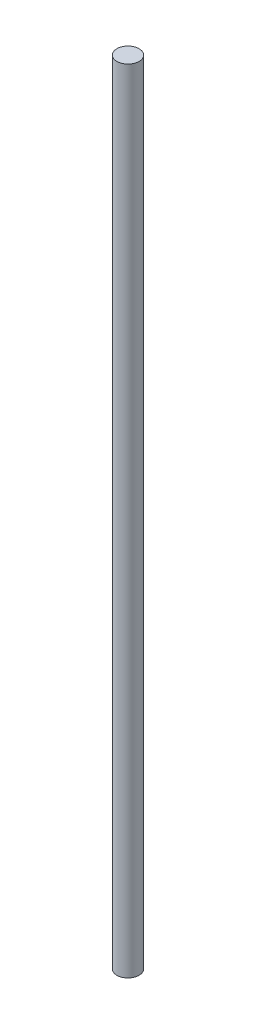
SolidWorks part; units mm, degrees
material "Alumina"
ref_plane "Front Plane" through (0, 0, 0) normal (0, 0, 1) x (1, 0, 0)
ref_plane "Top Plane" through (0, 0, 0) normal (0, 1, 0) x (1, 0, 0)
ref_plane "Right Plane" through (0, 0, 0) normal (1, 0, 0) x (0, 0, -1)
sketch "Sketch1" plane through (0, 0, 0) normal (0, 1, 0) x (1, 0, 0)
  circle A0 centre (0, 0) radius 14
  dimension "D1" = 28
extrude "Boss-Extrude1" add sketch "Sketch1" along normal blind 1000
